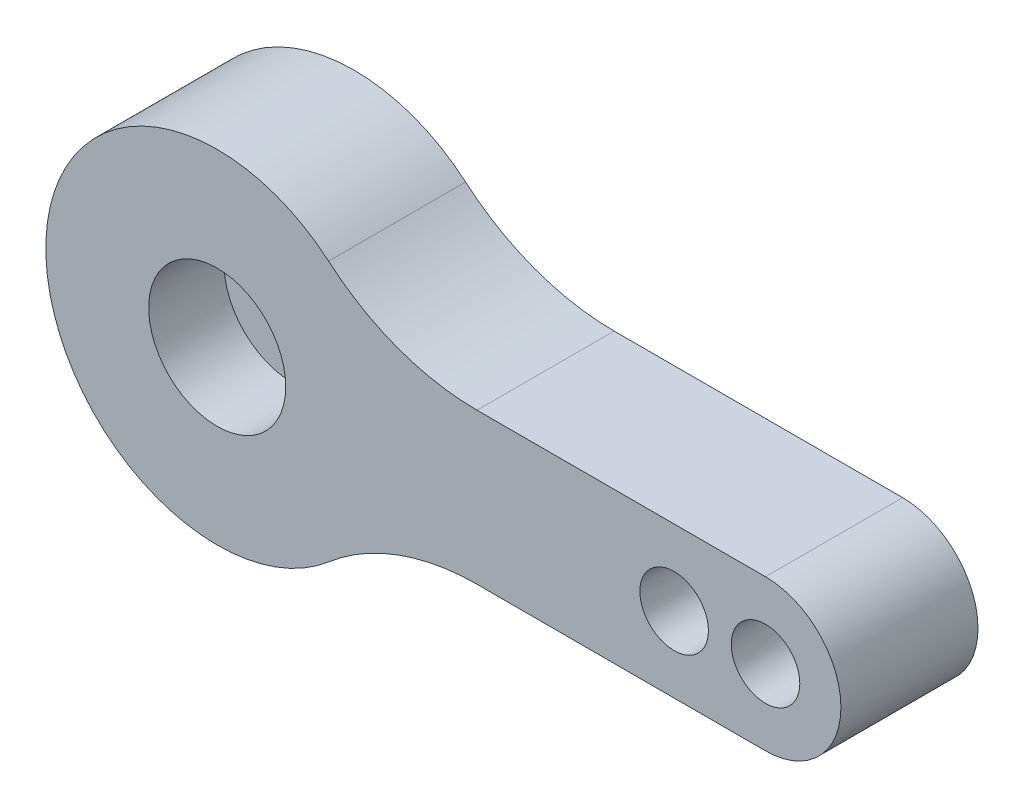
SolidWorks part; units mm, degrees
ref_plane "Спереди" through (0, 0, 0) normal (0, 0, 1) x (1, 0, 0)
ref_plane "Сверху" through (0, 0, 0) normal (0, 1, 0) x (1, 0, 0)
ref_plane "Справа" through (0, 0, 0) normal (1, 0, 0) x (0, 0, -1)
sketch "Эскиз1" plane through (0, 0, 0) normal (0, 0, 1) x (1, 0, 0)
  line L0 (24, 3.3) -> (11.3737, 3.3)
  line L1 (0, 0) -> (24, 0) construction
  line L2 (24, -3.3) -> (11.3737, -3.3)
  arc A0 (4.8744, 5.7) -> (4.8744, -5.7) centre (0, 0) ccw
  arc A1 (24, -3.3) -> (24, 3.3) centre (24, 0) ccw
  circle A2 centre (24, 0) radius 1.5
  circle A3 centre (20, 0) radius 1.5
  arc A4 (4.8744, 5.7) -> (11.3737, 3.3) centre (11.3737, 13.3) ccw
  arc A5 (4.8744, -5.7) -> (11.3737, -3.3) centre (11.3737, -13.3) cw
  circle A6 centre (0, 0) radius 1.5
  dimension "D1" = 15
  dimension "D2" = 6.6
  dimension "D3" = 3
  dimension "D5" = 10
  dimension "D4" = 4
  dimension "D6" = 20
extrude "Плечо основа" add sketch "Эскиз1" along normal blind 6
sketch "Эскиз2" plane through (0, 0, 6) normal (0, 0, 1) x (1, 0, 0)
  circle A0 centre (0, 0) radius 3
  dimension "D1" = 6
extrude "Под вал сервопривода" cut sketch "Эскиз2" against normal blind 3.3
